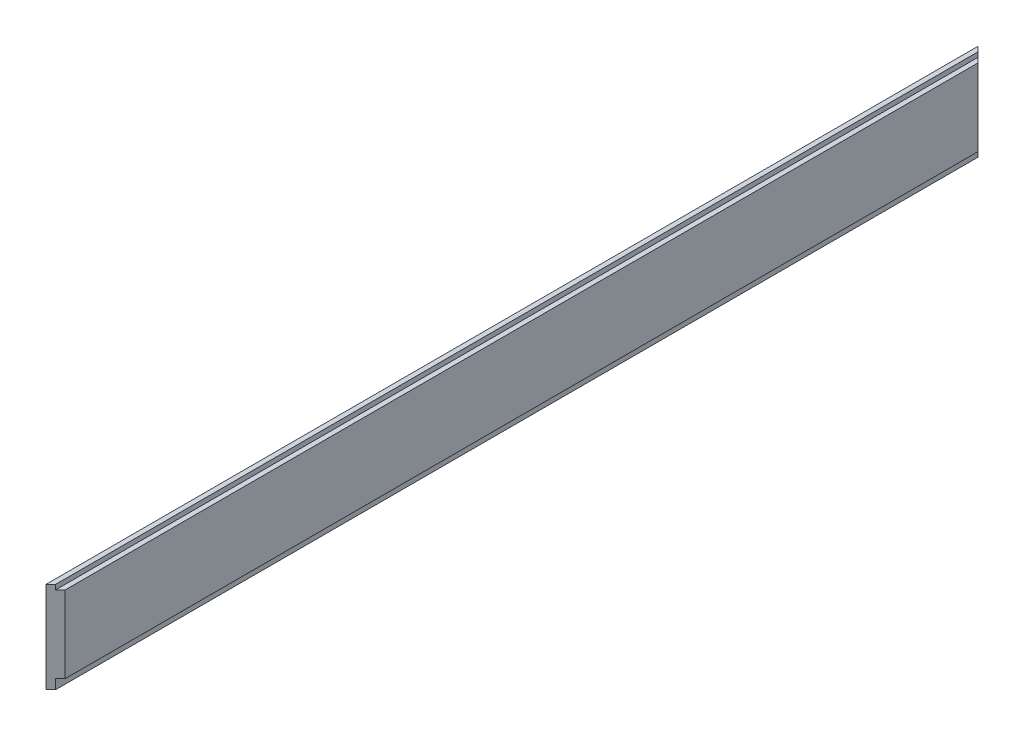
SolidWorks part; units mm, degrees
material "Pine"
ref_plane "Front Plane" through (0, 0, 0) normal (0, 0, 1) x (1, 0, 0)
ref_plane "Top Plane" through (0, 0, 0) normal (0, 1, 0) x (1, 0, 0)
ref_plane "Right Plane" through (0, 0, 0) normal (1, 0, 0) x (0, 0, -1)
sketch "Sketch1" plane through (0, 0, 0) normal (0, 0, 1) x (1, 0, 0)
  line L0 (0, 0) -> (0, 60.325)
  line L1 (0, 60.325) -> (3.175, 60.325)
  line L2 (3.175, 60.325) -> (3.175, 57.15)
  line L3 (3.175, 57.15) -> (6.35, 57.15)
  line L4 (6.35, 57.15) -> (6.35, 6.35)
  line L5 (6.35, 6.35) -> (3.175, 6.35)
  line L6 (3.175, 6.35) -> (3.175, 0)
  line L7 (3.175, 0) -> (0, 0)
  dimension "D1" = 6.35
  dimension ".125" = 3.175
  dimension "D2" = 3.175
  dimension "D3" = 3.175
  dimension "D4" = 3.175
  dimension "D5" = 50.8
extrude "Boss-Extrude1" add sketch "Sketch1" along normal blind 615.95 contours L0 L1 L2 L3 L4 L5 L6 L7
sketch "Sketch2" plane through (0, 60.325, 0) normal (0, 1, 0) x (1, 0, 0)
  line L4 (0, 0) -> (6.35, 0)
  line L5 (6.35, 0) -> (6.35, -6.35)
  line L6 (6.35, -615.95) -> (6.35, 0) construction
  line L7 (6.35, -6.35) -> (0, 0)
  dimension "D1" = 6.35
extrude "Cut-Extrude1" cut sketch "Sketch2" against normal through all
ref_plane "Plane1" through (0, 0, 307.975) normal (0, 0, 1) x (1, 0, 0)
mirror "Mirror1" about plane through (0, 0, 307.975) normal (0, 0, 1) of "Cut-Extrude1"
